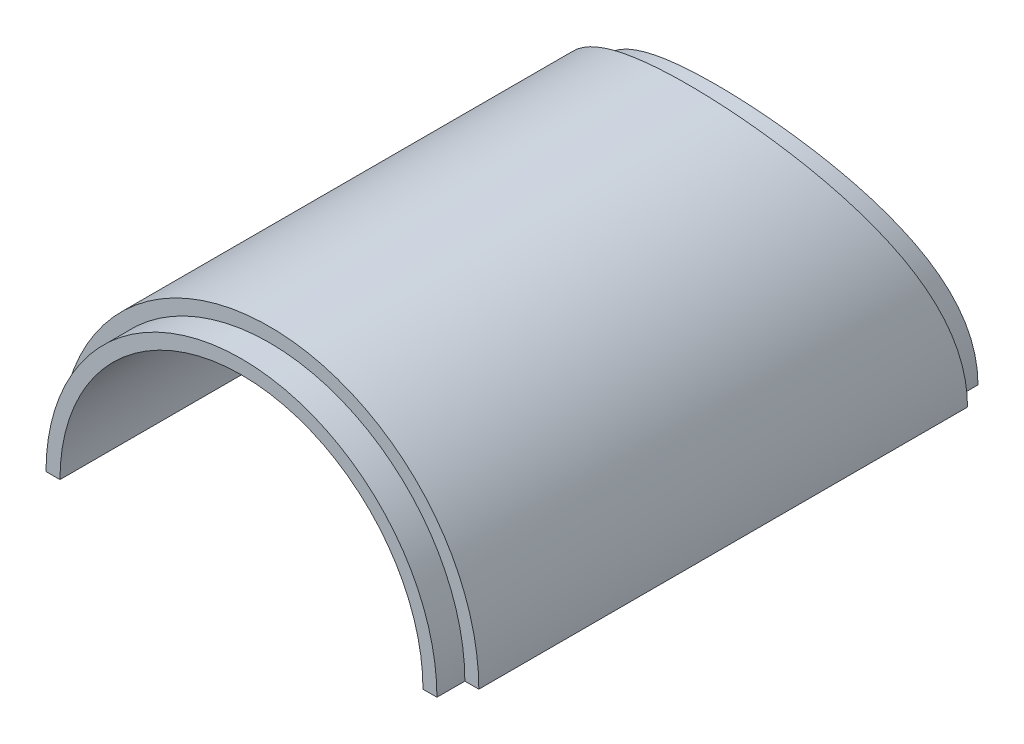
SolidWorks part; units mm, degrees
ref_plane "Front Plane" through (0, 0, 0) normal (0, 0, 1) x (1, 0, 0)
ref_plane "Top Plane" through (0, 0, 0) normal (0, 1, 0) x (1, 0, 0)
ref_plane "Right Plane" through (0, 0, 0) normal (1, 0, 0) x (0, 0, -1)
sketch "Sketch1" plane through (0, 0, 0) normal (0, 1, 0) x (1, 0, 0)
  line L0 (0, 0) -> (0, -30) construction
  line L1 (0, -30) -> (36, -30) construction
  line L2 (36, -30) -> (36, 0) construction
  line L3 (36, 0) -> (0, 0) construction
  line L4 (3, 0) -> (3, -30)
  line L5 (33, 0) -> (33, -30)
  line L6 (5, 0) -> (5, -30)
  line L7 (31, 0) -> (31, -30)
  dimension "D1" = 30
  dimension "D2" = 36
  dimension "D3" = 3
  dimension "D4" = 3
  dimension "D5" = 2
  dimension "D6" = 2
sketch "Sketch2" plane through (0, 0, 0) normal (0, 0, 1) x (1, 0, 0)
  line L0 (3, 0) -> (5, 0)
  line L1 (31, 0) -> (33, 0)
  arc A0 (3, 0) -> (33, 0) centre (18, 0) cw
  arc A1 (5, 0) -> (31, 0) centre (18, 0) cw
extrude "Boss-Extrude1" add sketch "Sketch2" along normal blind 30
sketch "Sketch3" plane through (0, 0, 0) normal (0, 0, 1) x (1, 0, 0)
  line L0 (3, 0) -> (5, 0)
  line L1 (31, 0) -> (33, 0)
  arc A0 (3, 0) -> (33, 0) centre (18, 0) cw
  arc A1 (5, 0) -> (31, 0) centre (18, 0) cw
extrude "Boss-Extrude2" add sketch "Sketch3" against normal blind 30
sketch "Sketch4" plane through (0, 0, 0) normal (0, 1, 0) x (1, 0, 0)
  line L0 (18, 0) -> (18, 25) construction
  line L1 (36, 0) -> (0, 0) construction
  circle A0 centre (18, 25) radius 25
  dimension "D1" = 25
extrude "Cut-Extrude2" cut sketch "Sketch4" along normal blind 30
ref_plane "GPS_END_PLANE" through (0, 0, 30) normal (0, 0, 1) x (1, 0, 0)
sketch "Sketch5" plane through (0, 0, 30) normal (0, 0, 1) x (1, 0, 0)
  line L0 (5, 0) -> (3, 0) construction
  line L1 (31, 0) -> (33, 0) construction
  line L2 (4, 0) -> (5, 0)
  line L3 (31, 0) -> (32, 0)
  arc A0 (5, 0) -> (31, 0) centre (18, 0) cw
  arc A1 (32, 0) -> (4, 0) centre (18, 0) ccw
extrude "Boss-Extrude3" add sketch "Sketch5" along normal blind 2
sketch "Sketch6" plane through (0, 0, 0) normal (0, 0, 1) x (1, 0, 0)
  line L0 (31, 0) -> (33, 0) construction
  line L1 (5, 0) -> (3, 0) construction
  line L2 (5, 0) -> (4, 0)
  line L3 (31, 0) -> (32, 0)
  arc A0 (32, 0) -> (4, 0) centre (18, 0) ccw
  arc A1 (5, 0) -> (31, 0) centre (18, 0) cw
extrude "Boss-Extrude4" add sketch "Sketch6" against normal blind 10
sketch "Sketch7" plane through (0, 0, 0) normal (0, 1, 0) x (1, 0, 0)
  line L0 (18, 0) -> (18, 25) construction
  line L1 (36, 0) -> (0, 0) construction
  circle A0 centre (18, 25) radius 23
  dimension "D2" = 46
  dimension "D1" = 25
extrude "Cut-Extrude4" cut sketch "Sketch7" along normal blind 27 contours A0
